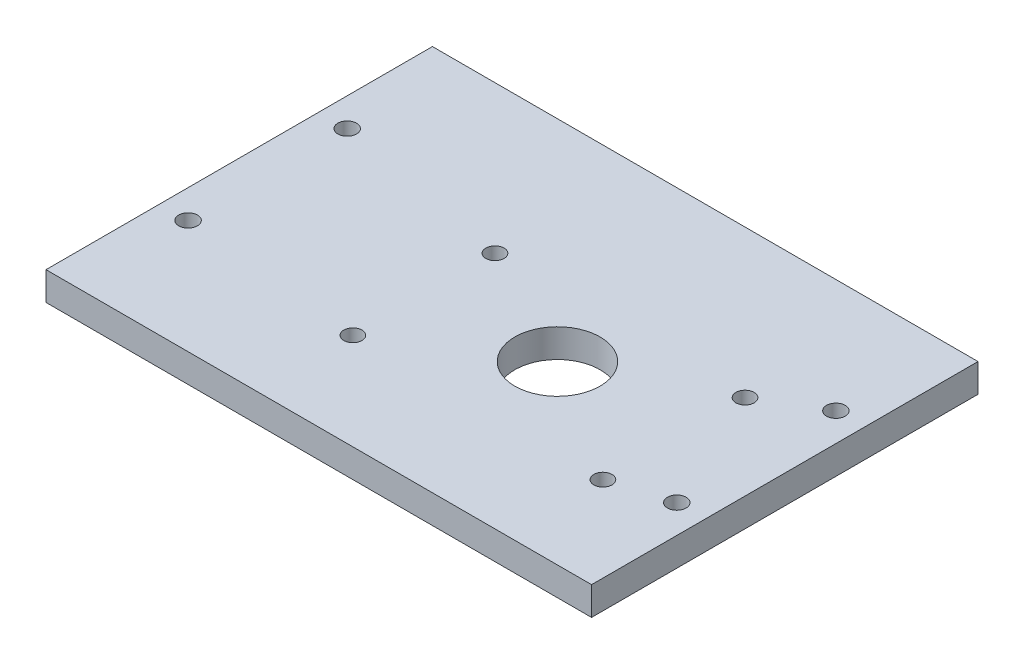
SolidWorks part; units mm, degrees
ref_plane "Front Plane" through (0, 0, 0) normal (0, 0, 1) x (1, 0, 0)
ref_plane "Top Plane" through (0, 0, 0) normal (0, 1, 0) x (1, 0, 0)
ref_plane "Right Plane" through (0, 0, 0) normal (1, 0, 0) x (0, 0, -1)
sketch "Sketch1" plane through (0, 0, 0) normal (0, 1, 0) x (1, 0, 0)
  line L0 (-55, 0) -> (55, 0) construction
  line L1 (-48, 34) -> (48, 34)
  line L2 (-48, 34) -> (-48, -34)
  line L3 (-48, -34) -> (48, -34)
  line L4 (48, 34) -> (48, -34)
  line L5 (0, -55) -> (0, 55) construction
  dimension "D1" = 96
  dimension "D2" = 68
  dimension "D3" = 34
  dimension "D4" = 48
extrude "Boss-Extrude1" add sketch "Sketch1" along normal blind 5
sketch "Sketch2" plane through (0, 5, 0) normal (0, 1, 0) x (1, 0, 0)
  line L0 (48, 34) -> (-48, 34) construction
  line L1 (-48, 34) -> (-48, -34) construction
  line L2 (-48, -34) -> (48, -34) construction
  line L3 (48, -34) -> (48, 34) construction
  line L5 (33, 44.9894) -> (33, -45.5363) construction
  line L6 (-59.8213, 8) -> (77.2228, 8) construction
  line L7 (73.994, -17) -> (-61.8543, -17) construction
  line L8 (-11, 42.4781) -> (-11, -44.6992) construction
  line L9 (11, 40.8039) -> (11, -45.5363) construction
  line L10 (64.5468, -3) -> (-57.0709, -3) construction
  circle A0 centre (-43, 14) radius 1.65
  circle A1 centre (43, 14) radius 1.65
  circle A2 centre (43, -14) radius 1.65
  circle A3 centre (-43, -14) radius 1.65
  circle A4 centre (-11, 8) radius 1.6
  circle A5 centre (33, 8) radius 1.6
  circle A6 centre (33, -17) radius 1.6
  circle A7 centre (-11, -17) radius 1.6
  circle A8 centre (11, -3) radius 7.5
  dimension "D3" = 3.3
  dimension "D6" = 3.2
  dimension "D7" = 3.2
  dimension "D15" = 3.2
  dimension "D8" = 3.2
  dimension "D10" = 15
  dimension "D1" = 20
  dimension "D2" = 5
  dimension "D9" = 20
  dimension "D11" = 15
  dimension "D12" = 26
  dimension "D13" = 25
  dimension "D14" = 44
  dimension "D16" = 37
  dimension "D17" = 37
  dimension "D4" = 2
  dimension "D5" = 2
extrude "Cut-Extrude1" cut sketch "Sketch2" against normal through all
